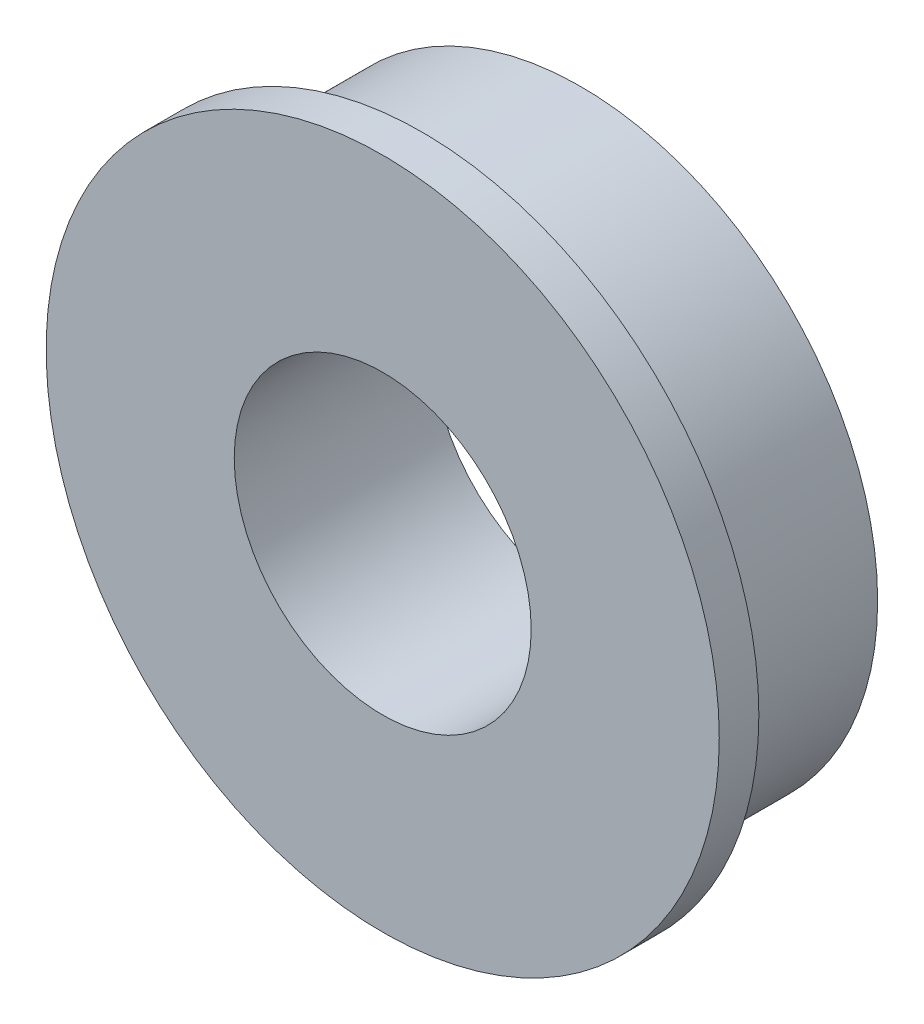
SolidWorks part; units mm, degrees
material "碳钢"
ref_plane "前视基准面" through (0, 0, 0) normal (0, 0, 1) x (1, 0, 0)
ref_plane "上视基准面" through (0, 0, 0) normal (0, 1, 0) x (1, 0, 0)
ref_plane "右视基准面" through (0, 0, 0) normal (1, 0, 0) x (0, 0, -1)
sketch "草图1" plane through (0, 0, 0) normal (0, 0, 1) x (1, 0, 0)
  circle A0 centre (0, 0) radius 6
  circle A1 centre (0, 0) radius 3
  dimension "D1" = 12
  dimension "D2" = 6
extrude "凸台-拉伸1" add sketch "草图1" along normal blind 3.2
sketch "草图2" plane through (0, 0, 3.2) normal (0, 0, 1) x (1, 0, 0)
  circle A0 centre (0, 0) radius 3
  circle A1 centre (0, 0) radius 6.8
  dimension "D1" = 6
  dimension "D2" = 13.6
extrude "凸台-拉伸2" add sketch "草图2" along normal blind 0.8
